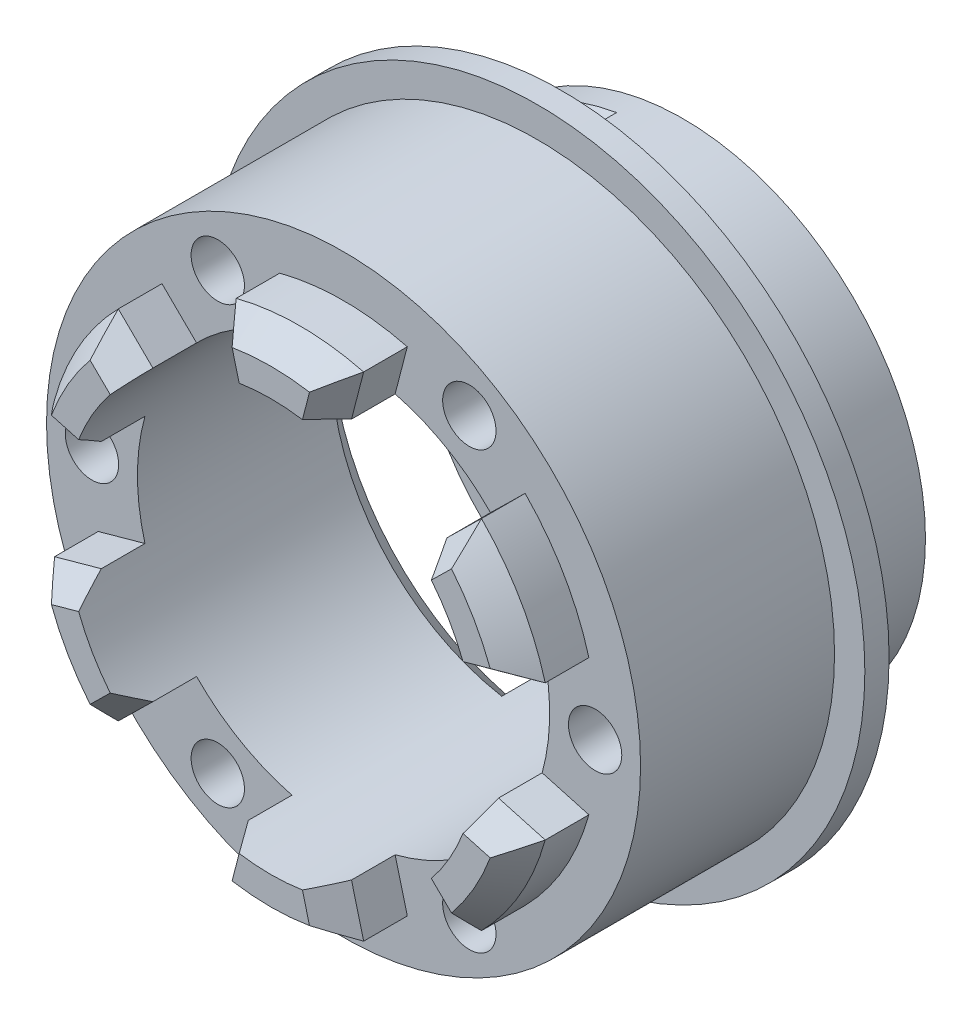
SolidWorks part; units mm, degrees
ref_plane "정면" through (0, 0, 0) normal (0, 0, 1) x (1, 0, 0)
ref_plane "윗면" through (0, 0, 0) normal (0, 1, 0) x (1, 0, 0)
ref_plane "우측면" through (0, 0, 0) normal (1, 0, 0) x (0, 0, -1)
sketch "스케치1" plane through (0, 0, 0) normal (0, 0, 1) x (1, 0, 0)
  circle A0 centre (0, 0) radius 10
  dimension "D1" = 20
extrude "보스-돌출1" add sketch "스케치1" along normal blind 2
sketch "스케치2" plane through (0, 0, 2) normal (0, 0, 1) x (1, 0, 0)
  circle A0 centre (0, 0) radius 10
  circle A1 centre (0, 0) radius 8.5
  circle A5 centre (0, 0) radius 10 construction
  dimension "D1" = 1.5
extrude "보스-돌출2" add sketch "스케치2" along normal blind 3
sketch "스케치4" plane through (0, 0, 5) normal (0, 0, 1) x (1, 0, 0)
  circle A0 centre (0, 0) radius 13.5
  circle A1 centre (0, 0) radius 8.5
  circle A2 centre (0, 0) radius 8.5 construction
  dimension "D1" = 27
extrude "보스-돌출3" add sketch "스케치4" along normal blind 1
sketch "스케치5" plane through (0, 0, 6) normal (0, 0, 1) x (1, 0, 0)
  circle A0 centre (0, 0) radius 8.5
  circle A1 centre (0, 0) radius 12.25
  circle A2 centre (0, 0) radius 8.5 construction
  dimension "D1" = 24.5
extrude "보스-돌출4" add sketch "스케치5" along normal blind 8
sketch "스케치6" plane through (0, 0, 14) normal (0, 0, 1) x (1, 0, 0)
  circle A0 centre (0, 0) radius 10.375 construction
  circle A6 centre (0, 0) radius 8.5 construction
  circle A8 centre (10.375, 0) radius 1.1
  circle A9 centre (5.1875, -8.985) radius 1.1
  circle A10 centre (-5.1875, -8.985) radius 1.1
  circle A11 centre (-10.375, 0) radius 1.1
  circle A12 centre (-5.1875, 8.985) radius 1.1
  circle A13 centre (5.1875, 8.985) radius 1.1
  point P19 (0, 0)
  point P20 (0, 0)
  dimension "D1" = 1.875
  dimension "D2" = 2.2
  dimension "D3" = 6
extrude "컷-돌출1" cut sketch "스케치6" against normal blind 8
sketch "스케치7" plane through (0, 0, 0) normal (0, 0, -1) x (-1, 0, 0)
  circle A0 centre (0, 0) radius 7 construction
  circle A5 centre (0, 0) radius 3
  circle A6 centre (-7, 0) radius 1.15
  circle A7 centre (7, 0) radius 1.15
  circle A9 centre (0, 7) radius 1.15
  circle A11 centre (0, -7) radius 1.15
  dimension "D1" = 14
  dimension "D2" = 2.3
  dimension "D4" = 6
extrude "컷-돌출2" cut sketch "스케치7" against normal through all
sketch "스케치10" plane through (0, 0, 14) normal (0, 0, 1) x (1, 0, 0)
  line L0 (-2.1282, 8.2293) -> (-2.629, 10.1656)
  line L2 (6.0626, 5.9577) -> (7.4891, 7.3595)
  line L4 (-8.1909, 2.2715) -> (-10.1181, 2.806)
  line L6 (8.1909, -2.2715) -> (10.1181, -2.806)
  line L8 (2.1282, -8.2293) -> (2.629, -10.1656)
  line L10 (-6.0626, -5.9577) -> (-7.4891, -7.3595)
  line L12 (-6.0626, 5.9577) -> (-7.4891, 7.3595)
  line L14 (2.1282, 8.2293) -> (2.629, 10.1656)
  line L16 (8.1909, 2.2715) -> (10.1181, 2.806)
  line L18 (6.0626, -5.9577) -> (7.4891, -7.3595)
  line L20 (-2.1282, -8.2293) -> (-2.629, -10.1656)
  line L22 (-8.1909, -2.2715) -> (-10.1181, -2.806)
  arc A0 (-7.4891, 7.3595) -> (-10.1181, 2.806) centre (0, 0) ccw
  arc A1 (-8.1909, -2.2715) -> (-6.0626, -5.9577) centre (0, 0) ccw
  arc A2 (2.629, 10.1656) -> (-2.629, 10.1656) centre (0, 0) ccw
  arc A3 (10.1181, 2.806) -> (7.4891, 7.3595) centre (0, 0) ccw
  arc A4 (7.4891, -7.3595) -> (10.1181, -2.806) centre (0, 0) ccw
  arc A5 (-2.629, -10.1656) -> (2.629, -10.1656) centre (0, 0) ccw
  arc A6 (-10.1181, -2.806) -> (-7.4891, -7.3595) centre (0, 0) ccw
  arc A7 (-2.1282, -8.2293) -> (2.1282, -8.2293) centre (0, 0) ccw
  arc A8 (6.0626, -5.9577) -> (8.1909, -2.2715) centre (0, 0) ccw
  arc A9 (8.1909, 2.2715) -> (6.0626, 5.9577) centre (0, 0) ccw
  arc A10 (2.1282, 8.2293) -> (-2.1282, 8.2293) centre (0, 0) ccw
  arc A11 (-6.0626, 5.9577) -> (-8.1909, 2.2715) centre (0, 0) ccw
  circle A12 centre (0, 0) radius 8.5 construction
  circle A13 centre (0, 0) radius 8.5 construction
  point P30 (0, 0)
  point P48 (0, 0)
  point P61 (0, 0)
  dimension "D1" = 2
extrude "보스-돌출5" add sketch "스케치10" along normal blind 3
chamfer "모따기1" distance 1.2 angle 35 18 edges at (-9.1545, -2.5388, 17) (-6.7759, -6.6586, 17) (-2.3786, -9.1974, 17) (2.3786, -9.1974, 17) (9.1545, -2.5388, 17) (6.7759, -6.6586, 17) (6.7759, 6.6586, 17) (9.1545, 2.5388, 17) (2.3786, 9.1974, 17) (-2.3786, 9.1974, 17) (-6.7759, 6.6586, 17) (-9.1545, 2.5388, 17) (-9.0933, -5.25, 17) (0, -10.5, 17) (9.0933, -5.25, 17) (9.0933, 5.25, 17) (0, 10.5, 17) (-9.0933, 5.25, 17)
sketch "스케치11" plane through (0, 0, 0) normal (0, 0, -1) x (-1, 0, 0)
  line L0 (0, 0) -> (1.7365, 9.8481)
  line L1 (0, 0) -> (1.7365, -9.8481)
  line L2 (0, 0) -> (10, 0) construction
  circle A0 centre (0, 0) radius 10
  circle M6 centre (7, 0) radius 1.15
  circle M9 centre (0, 0) radius 3
  circle M10 centre (0, 0) radius 10
  dimension "D1" = 80
  dimension "D2" = 80
extrude "컷-돌출3" cut sketch "스케치11" against normal blind 3 from offset 2 contours L2 A0 L0 M9 M6 | L2 L1 M9 M10 M6 offset against normal yes
chamfer "모따기2" distance 1 angle 45 2 edges at (-8.5, 0, 5) (-10, 0, 2)
